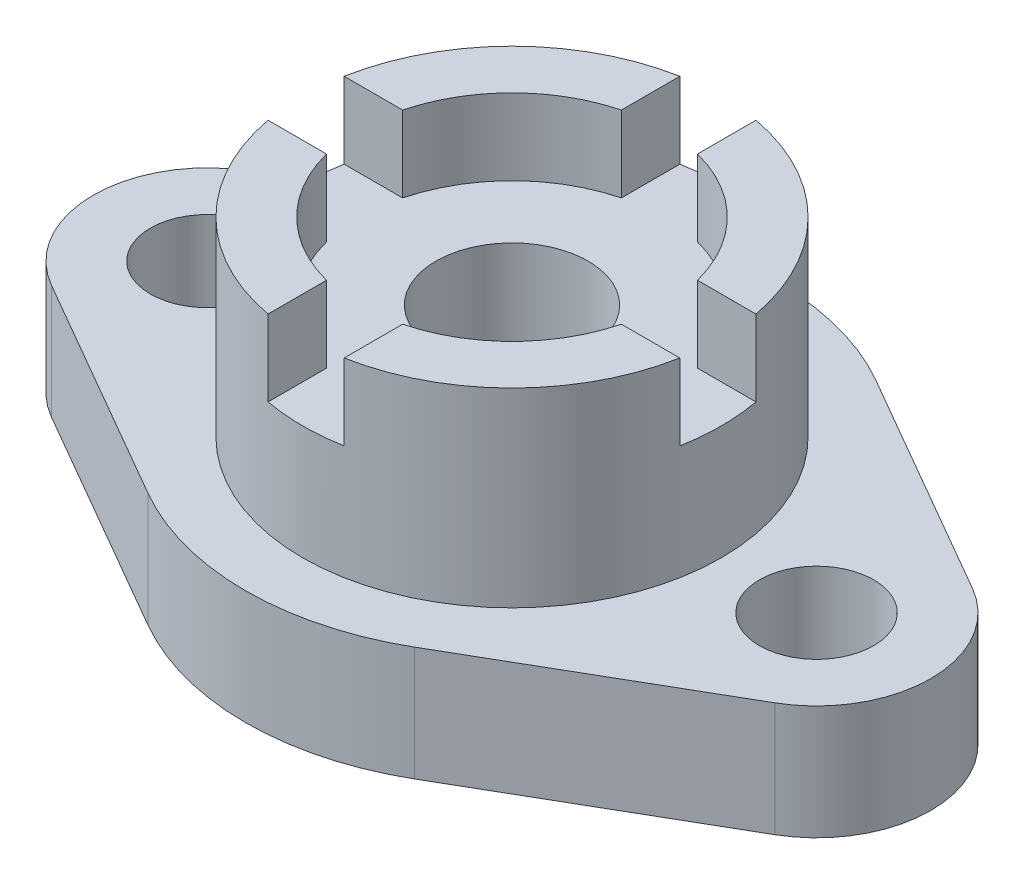
SolidWorks part; units mm, degrees
ref_plane "Front Plane" through (0, 0, 0) normal (0, 0, 1) x (1, 0, 0)
ref_plane "Top Plane" through (0, 0, 0) normal (0, 1, 0) x (1, 0, 0)
ref_plane "Right Plane" through (0, 0, 0) normal (1, 0, 0) x (0, 0, -1)
sketch "Sketch1" plane through (0, 0, 0) normal (0, 1, 0) x (1, 0, 0)
  line L0 (0, 2.5927) -> (0, -2.6949) construction
  line L1 (-2.375, 0.6495) -> (-0.875, 1.5155)
  line L2 (-2.375, -0.6495) -> (-0.875, -1.5155)
  line L3 (2.375, -0.6495) -> (0.875, -1.5155)
  line L4 (2.375, 0.6495) -> (0.875, 1.5155)
  arc A0 (-2.375, 0.6495) -> (-2.375, -0.6495) centre (-2, 0) ccw
  arc A1 (-0.875, -1.5155) -> (0.875, -1.5155) centre (0, 0) ccw
  arc A3 (0.875, 1.5155) -> (-0.875, 1.5155) centre (0, 0) ccw
  arc A4 (2.375, -0.6495) -> (2.375, 0.6495) centre (2, 0) ccw
  dimension "D2" = 1.5
  dimension "D3" = 3.5
  dimension "D1" = 4
extrude "Boss-Extrude1" add sketch "Sketch1" along normal blind 0.75
sketch "Sketch2" plane through (0, 0.75, 0) normal (0, 1, 0) x (1, 0, 0)
  circle A0 centre (-2, 0) radius 0.375
  circle A1 centre (2, 0) radius 0.375
  dimension "D1" = 0.75
  dimension "D2" = 4
  dimension "D3" = 2
extrude "Cut-Extrude1" cut sketch "Sketch2" against normal through all
sketch "Sketch3" plane through (0, 0.75, 0) normal (0, 1, 0) x (1, 0, 0)
  circle A0 centre (0, 0) radius 1.375
  dimension "D1" = 2.75
extrude "Boss-Extrude2" add sketch "Sketch3" along normal blind 1.25
sketch "Sketch5" plane through (0, 2, 0) normal (0, 1, 0) x (1, 0, 0)
  circle A0 centre (0, 0) radius 0.5
  dimension "D1" = 1
extrude "Cut-Extrude2" cut sketch "Sketch5" against normal through all
sketch "Sketch6" plane through (0, 2, 0) normal (0, 1, 0) x (1, 0, 0)
  line L0 (0, -1.8147) -> (0, 1.7454) construction
  line L1 (-1.7817, 0) -> (1.7636, 0) construction
  line L2 (0.25, 1.3521) -> (0.25, 0.9682)
  line L3 (-0.25, 1.3521) -> (-0.25, 0.9682)
  line L4 (-0.25, -1.3521) -> (-0.25, -0.9682)
  line L5 (0.25, -1.3521) -> (0.25, -0.9682)
  line L6 (-1.3521, -0.25) -> (-0.9682, -0.25)
  line L7 (-0.9682, 0.25) -> (-1.3521, 0.25)
  line L8 (1.3521, -0.25) -> (0.9682, -0.25)
  line L9 (0.9682, 0.25) -> (1.3521, 0.25)
  arc A0 (-0.25, 0.9682) -> (-0.9682, 0.25) centre (0, 0) ccw
  circle A1 centre (0, 0) radius 1.375 construction
  arc A2 (0.25, -0.9682) -> (0.9682, -0.25) centre (0, 0) ccw
  circle A3 centre (0, 0) radius 1.375 construction
  arc A4 (0.25, 1.3521) -> (-0.25, 1.3521) centre (0, 0) ccw
  arc A5 (-0.9682, -0.25) -> (-0.25, -0.9682) centre (0, 0) ccw
  arc A6 (0.9682, 0.25) -> (0.25, 0.9682) centre (0, 0) ccw
  arc A7 (-1.3521, 0.25) -> (-1.3521, -0.25) centre (0, 0) ccw
  arc A8 (-0.25, -1.3521) -> (0.25, -1.3521) centre (0, 0) ccw
  arc A9 (1.3521, -0.25) -> (1.3521, 0.25) centre (0, 0) ccw
  dimension "D1" = 2
  dimension "D2" = 0.5
  dimension "D3" = 0.5
extrude "Cut-Extrude3" cut sketch "Sketch6" against normal blind 0.5
